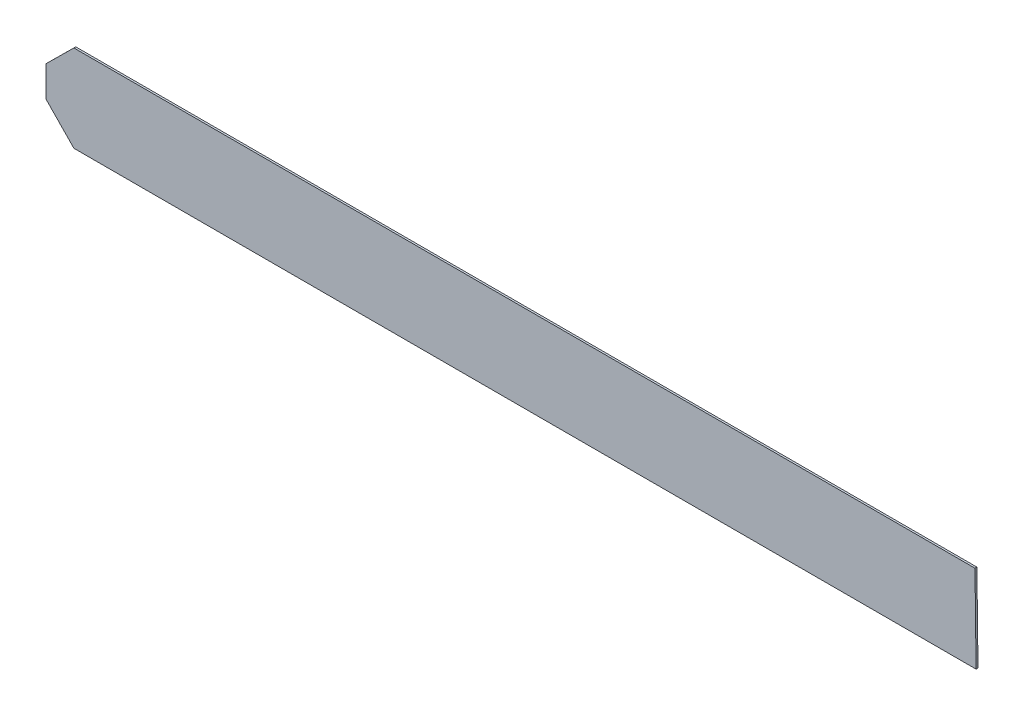
SolidWorks part; units mm, degrees
material "ASTM A500 Grade B"
ref_plane "Front Plane" through (0, 0, 0) normal (0, 0, 1) x (1, 0, 0)
ref_plane "Top Plane" through (0, 0, 0) normal (0, 1, 0) x (1, 0, 0)
ref_plane "Right Plane" through (0, 0, 0) normal (1, 0, 0) x (0, 0, -1)
sketch "Sketch1" plane through (0, 0, 0) normal (0, 0, 1) x (1, 0, 0)
  line L0 (4266.8117, -146.7903) -> (-216.4881, -146.7903)
  line L1 (4326.0867, -4804.2106) -> (4261.0214, 308.1754) construction
  line L2 (-216.4881, 285.0097) -> (-354.9957, 147.8379)
  line L4 (-354.9957, 147.8379) -> (-354.9957, -4.5621)
  line L6 (-354.9957, -4.5621) -> (-216.4881, -146.7903)
  line L7 (-216.4881, 285.0097) -> (4261.3162, 285.0097)
  line L8 (4261.3162, 285.0097) -> (4266.8117, -146.7903)
  dimension "D3" = 152.4
extrude "Boss-Extrude1" add sketch "Sketch1" along normal blind 9.525
fillet "Fillet1" [suppressed] radius 2.54
